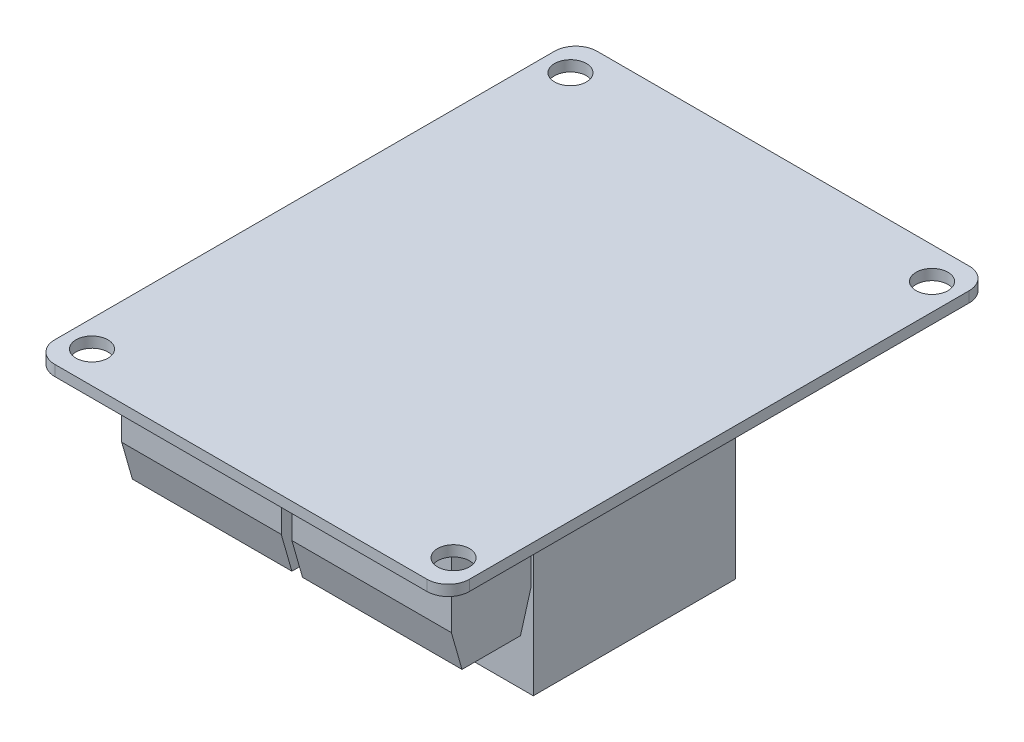
SolidWorks part; units mm, degrees
ref_plane "Front" through (0, 0, 0) normal (0, 0, 1) x (1, 0, 0)
ref_plane "Top" through (0, 0, 0) normal (0, 1, 0) x (1, 0, 0)
ref_plane "Right" through (0, 0, 0) normal (1, 0, 0) x (0, 0, -1)
sketch "Sketch1" plane through (0, 0, 0) normal (0, 1, 0) x (1, 0, 0)
  line L1 (-19.5, 25.5) -> (19.5, 25.5)
  line L2 (-19.5, 25.5) -> (-19.5, -25.5)
  line L3 (-19.5, -25.5) -> (19.5, -25.5)
  line L4 (19.5, 25.5) -> (19.5, -25.5)
  line L5 (-19.5, 25.5) -> (19.5, -25.5) construction
  line L6 (-19.5, -25.5) -> (19.5, 25.5) construction
  point P0 (0, 0)
  dimension "D1" = 39
  dimension "D2" = 51
extrude "Boss-Extrude1" add sketch "Sketch1" along normal blind 1
sketch "Sketch2" plane through (0, 1, 0) normal (0, 1, 0) x (1, 0, 0)
  line L0 (0, 25.5) -> (0, 0) construction
  line L1 (19.5, 25.5) -> (-19.5, 25.5) construction
  line L2 (0, 0) -> (19.5, 0) construction
  line L3 (19.5, -25.5) -> (19.5, 25.5) construction
  circle A0 centre (-17, 22.5) radius 1.5
  circle A1 centre (17, 22.5) radius 1.5
  circle A2 centre (17, -22.5) radius 1.5
  circle A3 centre (-17, -22.5) radius 1.5
  dimension "D1" = 34
  dimension "D2" = 45
  dimension "D3" = 3
extrude "Cut-Extrude1" cut sketch "Sketch2" against normal through all
fillet "Fillet1" radius 2 4 edges at (-19.5, 0.5, 25.5) (19.5, 0.5, 25.5) (19.5, 0.5, -25.5) (-19.5, 0.5, -25.5)
sketch "Sketch3" plane through (0, 0, 0) normal (0, -1, 0) x (1, 0, 0)
  line L0 (0, 0) -> (0, 25.5) construction
  line L1 (-15.5, 13.5) -> (-0.5, 13.5)
  line L2 (-15.5, 13.5) -> (-15.5, -5.5)
  line L3 (-15.5, -5.5) -> (-0.5, -5.5)
  line L4 (-0.5, 13.5) -> (-0.5, -5.5)
  line L5 (-17.5, 25.5) -> (17.5, 25.5) construction
  line L6 (0.5, 13.5) -> (0.5, -5.5)
  line L7 (15.5, -5.5) -> (0.5, -5.5)
  line L8 (15.5, 13.5) -> (15.5, -5.5)
  line L9 (15.5, 13.5) -> (0.5, 13.5)
  point P13 (2.1959, 0.4198)
  dimension "D1" = 19
  dimension "D2" = 15
  dimension "D3" = 1
  dimension "D4" = 12
extrude "Boss-Extrude2" add sketch "Sketch3" along normal blind 15.5
sketch "Sketch4" plane through (0, 0, 0) normal (0, -1, 0) x (1, 0, 0)
  line L0 (0, 0) -> (0, 25.5) construction
  line L1 (-15.5, 13.7) -> (-0.5, 13.7)
  line L2 (-15.5, 13.7) -> (-15.5, 21.2)
  line L3 (-15.5, 21.2) -> (-0.5, 21.2)
  line L4 (-0.5, 13.7) -> (-0.5, 21.2)
  line L5 (-17.5, 25.5) -> (17.5, 25.5) construction
  line L6 (0.5, 13.7) -> (0.5, 21.2)
  line L7 (15.5, 21.2) -> (0.5, 21.2)
  line L8 (15.5, 13.7) -> (15.5, 21.2)
  line L9 (15.5, 13.7) -> (0.5, 13.7)
  line L10 (-0.5, -5.5) -> (-0.5, 13.5) construction
  line L11 (-15.5, 13.5) -> (-15.5, -5.5) construction
  line L12 (-0.5, 13.5) -> (-15.5, 13.5) construction
  dimension "D1" = 0.2
  dimension "D2" = 7.5
extrude "Boss-Extrude3" add sketch "Sketch4" along normal blind 10
sketch "Sketch5" plane through (0, 0, 0) normal (1, 0, 0) x (0, 0, -1)
  line L0 (-17.45, -10) -> (-17.45, 0) construction
  line L1 (-13.7, -10) -> (-21.2, -10) construction
  line L2 (-13.7, 0) -> (-21.2, 0) construction
  line L3 (-21.2, -10) -> (-21.2, -6.5)
  line L4 (-21.2, -6.5) -> (-20.2, -10)
  line L5 (-20.2, -10) -> (-21.2, -10)
  line L6 (-14.7, -10) -> (-13.7, -10)
  line L7 (-13.7, -6.5) -> (-14.7, -10)
  line L8 (-13.7, -10) -> (-13.7, -6.5)
  dimension "D1" = 5.5
  dimension "D2" = 3.5
extrude "Cut-Extrude2" cut sketch "Sketch5" against normal through all both and the other way through all
sketch "Sketch6" plane through (0, 0, 0) normal (0, -1, 0) x (1, 0, 0)
  line L0 (17.5, -25.5) -> (-17.5, -25.5) construction
  line L1 (-11.5, -20.96) -> (-3.88, -20.96)
  line L2 (-11.5, -20.96) -> (-11.5, -23.5)
  line L3 (-11.5, -23.5) -> (-3.88, -23.5)
  line L4 (-3.88, -20.96) -> (-3.88, -23.5)
  line L5 (1.34, -20.96) -> (11.5, -20.96)
  line L6 (1.34, -20.96) -> (1.34, -23.5)
  line L7 (1.34, -23.5) -> (11.5, -23.5)
  line L8 (11.5, -20.96) -> (11.5, -23.5)
  line L9 (19.5, 23.5) -> (19.5, -23.5) construction
  line L10 (-19.5, -23.5) -> (-19.5, 23.5) construction
  dimension "D1" = 2.54
  dimension "D2" = 7.62
  dimension "D3" = 10.16
  dimension "D4" = 2
  dimension "D5" = 8
  dimension "D6" = 8
extrude "Boss-Extrude4" add sketch "Sketch6" along normal blind 2
sketch "Sketch7" plane through (0, -2, 0) normal (0, -1, 0) x (1, 0, 0)
  line L5 (11.5, -23.5) -> (11.5, -20.96) construction
  line L6 (11.5, -23.5) -> (11.5, -20.96) construction
  line L7 (7.44, -21.98) -> (7.44, -22.48)
  line L20 (7.94, -21.98) -> (7.44, -21.98)
  line L21 (0, -25.5) -> (0, 0) construction
  line L22 (17.5, -25.5) -> (-17.5, -25.5) construction
  line L23 (7.94, -21.98) -> (7.94, -22.48)
  line L24 (10.48, -22.48) -> (9.98, -21.98) construction
  line L25 (10.48, -21.98) -> (9.98, -22.48) construction
  line L38 (9.98, -21.98) -> (9.98, -22.48)
  line L39 (10.48, -22.48) -> (9.98, -22.48)
  line L40 (10.48, -21.98) -> (10.48, -22.48)
  line L41 (10.48, -21.98) -> (9.98, -21.98)
  line L42 (7.94, -22.48) -> (7.44, -22.48)
  line L43 (4.9, -21.98) -> (4.9, -22.48)
  line L44 (5.4, -21.98) -> (4.9, -21.98)
  line L45 (5.4, -21.98) -> (5.4, -22.48)
  line L46 (5.4, -22.48) -> (4.9, -22.48)
  line L47 (2.36, -21.98) -> (2.36, -22.48)
  line L48 (2.86, -21.98) -> (2.36, -21.98)
  line L49 (2.86, -21.98) -> (2.86, -22.48)
  line L50 (2.86, -22.48) -> (2.36, -22.48)
  line L51 (9.98, -21.98) -> (7.44, -21.98) construction
  line L52 (-9.98, -21.98) -> (-7.44, -21.98) construction
  line L53 (-10.48, -21.98) -> (-9.98, -22.48) construction
  line L54 (-10.48, -22.48) -> (-9.98, -21.98) construction
  line L55 (-5.4, -22.48) -> (-4.9, -22.48)
  line L56 (-5.4, -21.98) -> (-5.4, -22.48)
  line L57 (-5.4, -21.98) -> (-4.9, -21.98)
  line L58 (-4.9, -21.98) -> (-4.9, -22.48)
  line L59 (-7.94, -22.48) -> (-7.44, -22.48)
  line L60 (-7.94, -21.98) -> (-7.94, -22.48)
  line L61 (-7.94, -21.98) -> (-7.44, -21.98)
  line L62 (-7.44, -21.98) -> (-7.44, -22.48)
  line L63 (-10.48, -22.48) -> (-9.98, -22.48)
  line L64 (-10.48, -21.98) -> (-10.48, -22.48)
  line L65 (-10.48, -21.98) -> (-9.98, -21.98)
  line L66 (-9.98, -21.98) -> (-9.98, -22.48)
  point P4 (11.5, -22.23)
  point P43 (-10.23, -22.23)
  point P45 (10.23, -22.23)
  dimension "D1" = 1.27
  dimension "D2" = 0.5
  dimension "D3" = 2.54
extrude "Boss-Extrude5" add sketch "Sketch7" along normal blind 6
